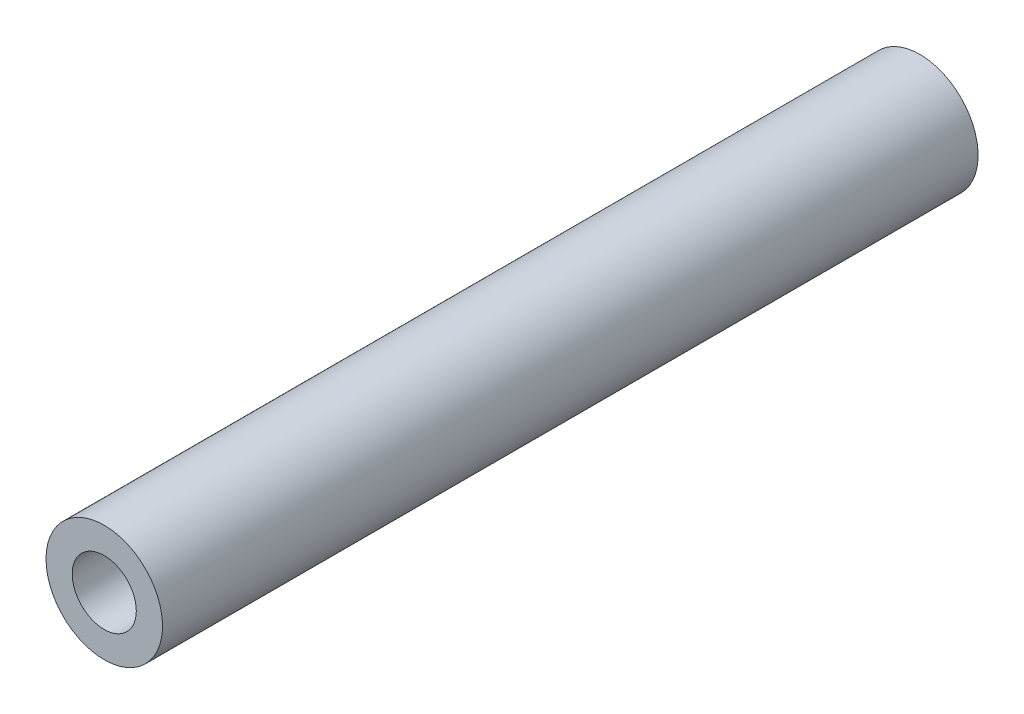
SolidWorks part; units mm, degrees
material "6061 合金"
ref_plane "前视基准面" through (0, 0, 0) normal (0, 0, 1) x (1, 0, 0)
ref_plane "上视基准面" through (0, 0, 0) normal (0, 1, 0) x (1, 0, 0)
ref_plane "右视基准面" through (0, 0, 0) normal (1, 0, 0) x (0, 0, -1)
sketch "草图1" plane through (0, 0, 0) normal (0, 0, 1) x (1, 0, 0)
  circle A1 centre (0, 0) radius 3
  dimension "D1" = 6
extrude "凸台-拉伸1" add sketch "草图1" along normal blind 42
hole_wizard "M4 螺纹孔1" positions "草图2" profile "草图3" tap size "M4" standard "GB" end condition through all
sketch "草图2" plane through (0, 0, 42) normal (0, 0, 1) x (1, 0, 0)
  point P0 (0, 0)
sketch "草图3" plane through (0, 0, 42) normal (1, 0, 0) x (0, -1, 0)
  line L0 (0, 0) -> (0, 42)
  line L1 (0, 42) -> (1.65, 42)
  line L2 (1.65, 42) -> (1.65, 0)
  line L5 (1.65, 0) -> (0, 0)
  line L11 (0, -6.35) -> (0, 107.95) construction
  dimension "通孔螺纹孔钻头直径" = 3.3
  dimension "通孔螺纹孔钻头深度" = 42
cosmetic thread "孔螺蚊线1"
